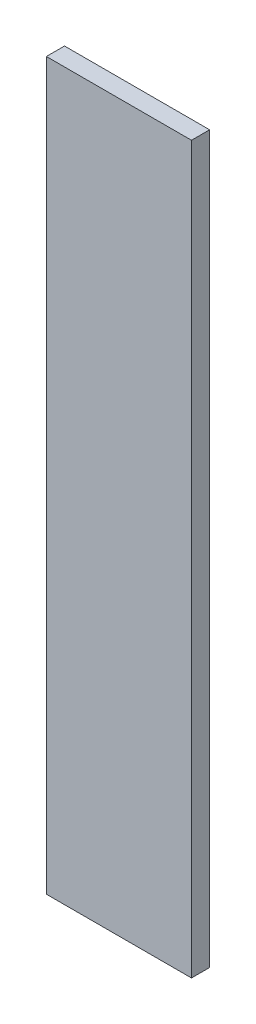
SolidWorks part; units mm, degrees
material "Pin"
ref_plane "Front" through (0, 0, 0) normal (0, 0, 1) x (1, 0, 0)
ref_plane "Top" through (0, 0, 0) normal (0, 1, 0) x (1, 0, 0)
ref_plane "Right" through (0, 0, 0) normal (1, 0, 0) x (0, 0, -1)
sketch "Esquisse1" plane through (0, 0, 0) normal (0, 0, 1) x (1, 0, 0)
  line L1 (-25.4, 127) -> (25.4, 127)
  line L2 (-25.4, 127) -> (-25.4, -127)
  line L3 (-25.4, -127) -> (25.4, -127)
  line L4 (25.4, 127) -> (25.4, -127)
  line L5 (-25.4, 127) -> (25.4, -127) construction
  line L6 (-25.4, -127) -> (25.4, 127) construction
  point P0 (0, 0)
  dimension "D1" = 254
  dimension "D2" = 50.8
extrude "Boss.-Extru.1" add sketch "Esquisse1" along normal blind 6.35
